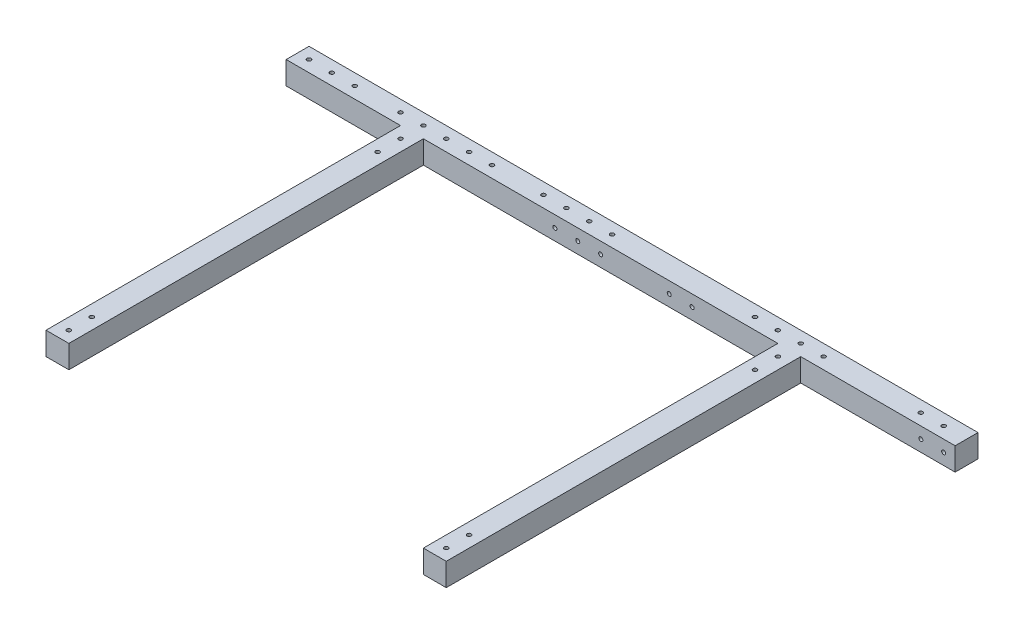
SolidWorks part; units mm, degrees
ref_plane "前视基准面" through (0, 0, 0) normal (0, 0, 1) x (1, 0, 0)
ref_plane "上视基准面" through (0, 0, 0) normal (0, 1, 0) x (1, 0, 0)
ref_plane "右视基准面" through (0, 0, 0) normal (1, 0, 0) x (0, 0, -1)
sketch "草图1" plane through (0, 0, 0) normal (0, 1, 0) x (1, 0, 0)
  line L1 (-175, 10) -> (175, 10)
  line L2 (-175, 10) -> (-175, -10)
  line L3 (-175, -10) -> (175, -10)
  line L4 (175, 10) -> (175, -10)
  line L5 (-175, 10) -> (175, -10) construction
  line L6 (-175, -10) -> (175, 10) construction
  line L7 (-175, -10) -> (-155, -10)
  line L8 (-175, -10) -> (-175, -320)
  line L9 (-175, -320) -> (-155, -320)
  line L10 (-155, -10) -> (-155, -320)
  line L11 (175, -10) -> (155, -10)
  line L12 (175, -10) -> (175, -320)
  line L13 (175, -320) -> (155, -320)
  line L14 (155, -10) -> (155, -320)
  line L15 (-175, 10) -> (-275, 10)
  line L16 (-175, 10) -> (-175, -10)
  line L17 (-175, -10) -> (-275, -10)
  line L18 (-275, 10) -> (-275, -10)
  point P0 (0, 0)
  dimension "D1" = 20
  dimension "D2" = 20
  dimension "D3" = 20
  dimension "D4" = 330
  dimension "D5" = 350
  dimension "D6" = 100
extrude "凸台-拉伸1" add sketch "草图1" along normal blind 20 contours L4 L1 L2 L3 | L10 L3 L8 L9 | L3 L14 L13 L12 | L16 L15 L18 L17
sketch "草图2" plane through (0, 20, 0) normal (0, 1, 0) x (1, 0, 0)
  line L0 (0, 0) -> (0, -41.9275) construction
  line L1 (-275, 10) -> (175, 10) construction
  line L2 (-175, -320) -> (-155, -320) construction
  line L3 (-165, 0) -> (-185, 0) construction
  line L4 (-175, 10) -> (-155, 10)
  line L5 (-175, 10) -> (-175, -320)
  line L6 (-175, -320) -> (-155, -320)
  line L7 (-155, 10) -> (-155, -320)
  line L8 (175, 10) -> (155, 10)
  line L9 (175, 10) -> (175, -320)
  line L10 (175, -320) -> (155, -320)
  line L11 (155, 10) -> (155, -320)
  line L12 (-155, 10) -> (155, 10)
  line L13 (-155, 10) -> (-155, -10)
  line L14 (-155, -10) -> (155, -10)
  line L15 (155, 10) -> (155, -10)
  line L16 (-165, -20) -> (-165, -40) construction
  line L17 (-125, 0) -> (-105, 0) construction
  circle A0 centre (-165, -310) radius 1.75
  circle A1 centre (-165, -290) radius 1.75
  circle A2 centre (-165, -20) radius 1.75
  circle A3 centre (-165, 0) radius 1.75
  circle A4 centre (-145, 0) radius 1.75
  circle A5 centre (-125, 0) radius 1.75
  circle A6 centre (165, -310) radius 1.75
  circle A7 centre (165, -290) radius 1.75
  circle A8 centre (165, -20) radius 1.75
  circle A9 centre (165, 0) radius 1.75
  circle A10 centre (145, 0) radius 1.75
  circle A11 centre (125, 0) radius 1.75
  circle A12 centre (-185, 0) radius 1.75
  circle A13 centre (-165, -40) radius 1.75
  circle A14 centre (-105, 0) radius 1.75
  dimension "D1" = 10
  dimension "D7" = 3.5
  dimension "D2" = 20
  dimension "D3" = 20
  dimension "D4" = 20
  dimension "D5" = 20
  dimension "D6" = 10
  dimension "D8" = 10
  dimension "D9" = 2
  dimension "D10" = 20
  dimension "D12" = 20
  dimension "D13" = 20
  dimension "D15" = 20
  dimension "D11" = 2
  dimension "D14" = 2
extrude "切除-拉伸1" cut sketch "草图2" against normal up to next contours A4 | A5 | A0 | A11 | A10 | A9 | A8 | A7 | A6 | A14 | A3 | A2 | A1 | A12 | A13
sketch "草图3" plane through (175, 0, 0) normal (1, 0, 0) x (0, 0, -1)
  line L0 (10, 0) -> (-320, 0) construction
  line L1 (10, 20) -> (-10, 20)
  line L2 (10, 20) -> (10, 0)
  line L3 (10, 0) -> (-10, 0)
  line L4 (-10, 20) -> (-10, 0)
  dimension "D1" = 20
extrude "凸台-拉伸2" add sketch "草图3" along normal blind 135
sketch "草图4" plane through (0, 20, 0) normal (0, 1, 0) x (1, 0, 0)
  line L0 (-275, 10) -> (310, 10) construction
  line L1 (175, -10) -> (175, -320) construction
  line L2 (310, -10) -> (175, -10) construction
  circle A0 centre (165, -40) radius 1.75
  circle A1 centre (185, 0) radius 1.75
  dimension "D1" = 50
  dimension "D3" = 3.5
  dimension "D2" = 10
  dimension "D4" = 10
  dimension "D5" = 10
extrude "切除-拉伸2" cut sketch "草图4" against normal blind 20
sketch "草图5" plane through (0, 0, -10) normal (0, 0, -1) x (-1, 0, 0)
  line L0 (175, 20) -> (175, 0) construction
  line L1 (40, 10) -> (20, 10) construction
  line L2 (275, 0) -> (-310, 0) construction
  circle A0 centre (40, 10) radius 1.75
  circle A1 centre (20, 10) radius 1.75
  circle A2 centre (0, 10) radius 1.75
  dimension "D1" = 135
  dimension "D2" = 3.5
  dimension "D4" = 20
  dimension "D5" = 10
  dimension "D3" = 3
extrude "切除-拉伸3" cut sketch "草图5" against normal up to next
sketch "草图6" plane through (0, 0, -10) normal (0, 0, -1) x (-1, 0, 0)
  line L0 (275, 20) -> (-310, 20) construction
  line L1 (-310, 0) -> (-310, 20) construction
  circle A0 centre (-300, 10) radius 1.75
  circle A1 centre (-280, 10) radius 1.75
  dimension "D1" = 10
  dimension "D4" = 3.5
  dimension "D2" = 10
  dimension "D3" = 20
extrude "切除-拉伸4" cut sketch "草图6" against normal up to next
sketch "草图7" plane through (0, 0, -10) normal (0, 0, -1) x (-1, 0, 0)
  line L0 (275, 20) -> (-310, 20) construction
  line L1 (-310, 0) -> (-310, 20) construction
  circle A0 centre (-80, 10) radius 1.75
  circle A1 centre (-60, 10) radius 1.75
  dimension "D1" = 20
  dimension "D3" = 3.5
  dimension "D2" = 10
  dimension "D4" = 230
extrude "切除-拉伸5" cut sketch "草图7" against normal blind 20
sketch "草图8" plane through (0, 0, 0) normal (0, -1, 0) x (1, 0, 0)
  line L0 (-60, 0) -> (-40, 0) construction
  line L1 (-155, 10) -> (155, 10) construction
  line L2 (310, 10) -> (175, 10) construction
  line L3 (310, 10) -> (310, -10) construction
  line L4 (290, 0) -> (270, 0) construction
  line L5 (-175, 10) -> (-275, 10) construction
  line L6 (-275, -10) -> (-275, 10) construction
  line L7 (-265, 0) -> (-245, 0) construction
  circle A0 centre (-60, 0) radius 1.75
  circle A2 centre (-40, 0) radius 1.75
  circle A3 centre (-20, 0) radius 1.75
  circle A4 centre (0, 0) radius 1.75
  circle A5 centre (290, 0) radius 1.75
  circle A6 centre (270, 0) radius 1.75
  circle A7 centre (-265, 0) radius 1.75
  circle A8 centre (-245, 0) radius 1.75
  circle A9 centre (-225, 0) radius 1.75
  point P17 (0, 0)
  dimension "D1" = 4
  dimension "D5" = 10
  dimension "D7" = 3.5
  dimension "D8" = 2
  dimension "D10" = 10
  dimension "D2" = 20
  dimension "D3" = 10
  dimension "D4" = 0
  dimension "D6" = 20
  dimension "D9" = 20
  dimension "D11" = 10
  dimension "D13" = 20
  dimension "D12" = 3
extrude "切除-拉伸6" cut sketch "草图8" against normal blind 20
